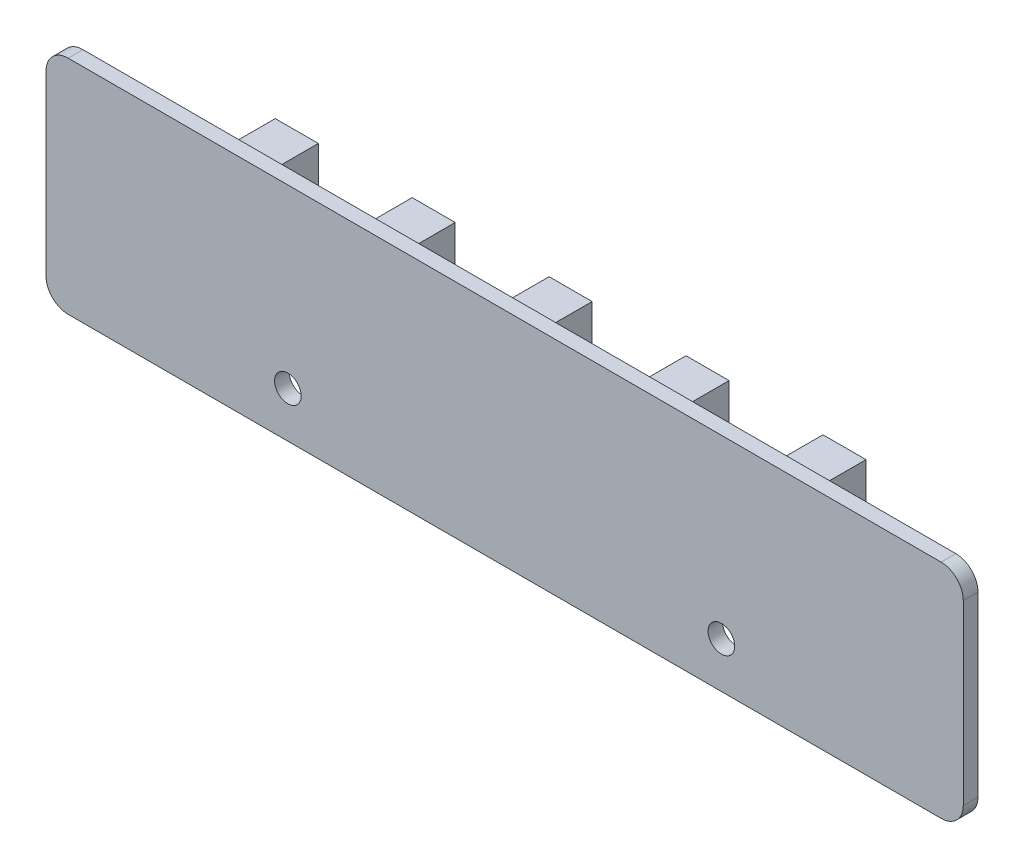
SolidWorks part; units mm, degrees
ref_plane "Plan de face" through (0, 0, 0) normal (0, 0, 1) x (1, 0, 0)
ref_plane "Plan de dessus" through (0, 0, 0) normal (0, 1, 0) x (1, 0, 0)
ref_plane "Plan de droite" through (0, 0, 0) normal (1, 0, 0) x (0, 0, -1)
sketch "Esquisse2" plane through (0, 0, 0) normal (0, 0, 1) x (1, 0, 0)
  line L5 (-46.6281, 77.0596) -> (71.3719, 77.0596)
  line L6 (-49.6281, 74.0596) -> (-49.6281, 50.0596)
  line L7 (-46.6281, 47.0596) -> (71.3719, 47.0596)
  line L8 (74.3719, 74.0596) -> (74.3719, 50.0596)
  arc A0 (-49.6281, 50.0596) -> (-46.6281, 47.0596) centre (-46.6281, 50.0596) ccw
  arc A1 (71.3719, 47.0596) -> (74.3719, 50.0596) centre (71.3719, 50.0596) ccw
  arc A2 (71.3719, 77.0596) -> (74.3719, 74.0596) centre (71.3719, 74.0596) cw
  arc A3 (-46.6281, 77.0596) -> (-49.6281, 74.0596) centre (-46.6281, 74.0596) ccw
  point P8 (74.3719, 47.0596)
  point P11 (74.3719, 77.0596)
  point P14 (-49.6281, 77.0596)
  dimension "D3" = 3
  dimension "D1" = 124
  dimension "D2" = 30
extrude "Boss.-Extru.1" add sketch "Esquisse2" along normal blind 1.99 contours L5 A2 L8 A1 L7 A0 L6 A3
sketch "Esquisse3" plane through (0, 0, 0) normal (0, 0, -1) x (-1, 0, 0)
  line L0 (46.6281, 77.0596) -> (-71.3719, 77.0596) construction
  line L1 (-15.2819, 75.0596) -> (-9.4619, 75.0596)
  line L2 (-15.2819, 75.0596) -> (-15.2819, 65.4296)
  line L3 (-15.2819, 65.4296) -> (-9.4619, 65.4296)
  line L4 (-9.4619, 75.0596) -> (-9.4619, 65.4296)
  line L5 (46.6281, 47.0596) -> (-71.3719, 47.0596) construction
  line L6 (49.6281, 74.0596) -> (49.6281, 50.0596) construction
  point P4 (-12.3719, 70.2446)
  point P5 (49.6281, 63.2571)
  point P6 (-12.3719, 47.0596)
  point P7 (-12.3719, 62.0596)
  dimension "D1" = 9.63
  dimension "D2" = 5.82
  dimension "D3" = 4.815
  dimension "D4" = 2.91
  dimension "D5" = 0
  dimension "D6" = 62
  dimension "D7" = 15
  dimension "D8" = 2
other "AlignerGroupe1"
extrude "Boss.-Extru.5" add sketch "Esquisse3" along normal blind 6.93
pattern_linear "Répétition linéaire2" count 3 spacing 18.509 along (-1, 0, 0) count 3 spacing 18.509 along (1, 0, 0) of "Boss.-Extru.5"
sketch "Esquisse6" plane through (0, 0, 0) normal (0, 0, -1) x (-1, 0, 0)
  line L0 (-74.3719, 74.0596) -> (-74.3719, 50.0596) construction
  line L1 (46.6281, 47.0596) -> (-71.3719, 47.0596) construction
  line L2 (-12.3719, 47.0596) -> (-12.3719, 77.0596)
  line L3 (46.6281, 77.0596) -> (-71.3719, 77.0596) construction
  circle A0 centre (-41.6719, 53.2396) radius 1.46
  circle A1 centre (16.9281, 53.2396) radius 1.46
  point P0 (-41.6719, 53.2396)
  point P10 (16.9281, 53.2396)
  point P12 (-41.6719, 53.2396)
  dimension "D1" = 32.7
  dimension "D2" = 6.18
  dimension "D3" = 2.92
hole_wizard "Dégagement M31" positions "Esquisse6" profile "Esquisse9" hole size "M3" standard "Ansi Metric" end condition through all
sketch "Esquisse9" plane through (41.6719, 53.2396, 0) normal (1, 0, 0) x (0, 1, 0)
  line L0 (0, 0) -> (0, 1.99)
  line L1 (0, 1.99) -> (1.8, 1.99)
  line L2 (1.8, 1.99) -> (1.8, 0)
  line L5 (1.8, 0) -> (0, 0)
  line L11 (0, -6.35) -> (0, 107.95) construction
  dimension "Diamètre du perçage jusqu'au prochain" = 3.6
  dimension "Profondeur du perçage jusqu'au prochain" = 1.99
